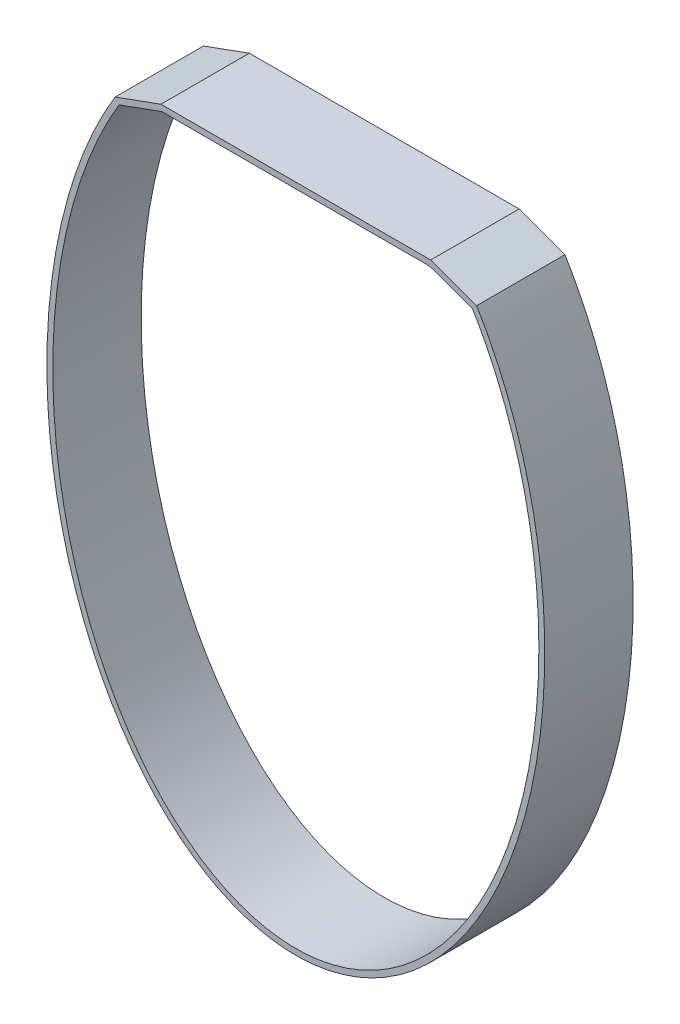
SolidWorks part; units mm, degrees
material "ABS"
ref_plane "Front Plane" through (0, 0, 0) normal (0, 0, 1) x (1, 0, 0)
ref_plane "Top Plane" through (0, 0, 0) normal (0, 1, 0) x (1, 0, 0)
ref_plane "Right Plane" through (0, 0, 0) normal (1, 0, 0) x (0, 0, -1)
sketch "Sketch1" plane through (0, 0, 0) normal (0, 0, 1) x (1, 0, 0)
  line L0 (-60, -5.3021) -> (60, -5.3021) construction
  line L1 (-45.4326, 0) -> (45.4326, 0)
  line L2 (-45.4326, 0) -> (-60, -5.3021)
  line L3 (45.4326, 0) -> (60, -5.3021)
  line L4 (0, -94.0287) -> (0, 0) construction
  line L5 (45.7853, 2) -> (61.3455, -3.6635)
  line L6 (-45.7853, 2) -> (45.7853, 2)
  line L7 (-45.7853, 2) -> (-61.3455, -3.6635)
  ellipse E0 centre (0, -94.0287) end of major axis (0, 35.2447) minor radius 82.5 (-60, -5.3021) -> (60, -5.3021) ccw
  spline S0 degree 1 poles (-61.3455, -3.6635) (61.3455, -3.6635) knots 0 0 1 1 construction
  spline S1 degree 3 poles (-61.3455, -3.6635) (-62.0546, -4.8259) (-63.4282, -7.162) (-66.0807, -12.0152) (-69.1723, -18.3435) (-72.5183, -26.3371) (-76.4682, -37.465) (-80.4105, -52.1508) (-83.4538, -70.6473) (-84.7485, -89.6316) (-84.1111, -115.0671) (-78.8879, -146.0908) (-66.0232, -178.9982) (-47.5783, -204.8501) (-24.9711, -221.4574) (0, -227.2244) (24.9711, -221.4574) (47.5783, -204.8501) (66.0232, -178.9982) (78.8879, -146.0908) (84.1111, -115.0671) (84.7485, -89.6316) (83.4538, -70.6473) (80.4105, -52.1508) (76.4682, -37.465) (72.5183, -26.3371) (69.1723, -18.3435) (66.0807, -12.0152) (63.4282, -7.162) (62.0546, -4.8259) (61.3455, -3.6635) knots 0.80797 0.80797 0.80797 0.80797 0.844432 0.880895 0.953821 1.026747 1.099672 1.245524 1.391375 1.537227 1.683078 1.974781 2.266484 2.558187 2.84989 3.141593 3.433296 3.724998 4.016701 4.308404 4.600107 4.745959 4.89181 5.037661 5.183513 5.256439 5.329364 5.40229 5.438753 5.475216 5.475216 5.475216 5.475216
  point P2 (0, -5.3021)
  point P6 (0, 0)
  dimension "D1" = 120
  dimension "D2" = 14.5674
  dimension "D3" = 5.3021
  dimension "D4" = 218
  dimension "D5" = 165
  dimension "D6" = 2
extrude "Boss-Extrude1" add sketch "Sketch1" along normal mid plane 30
